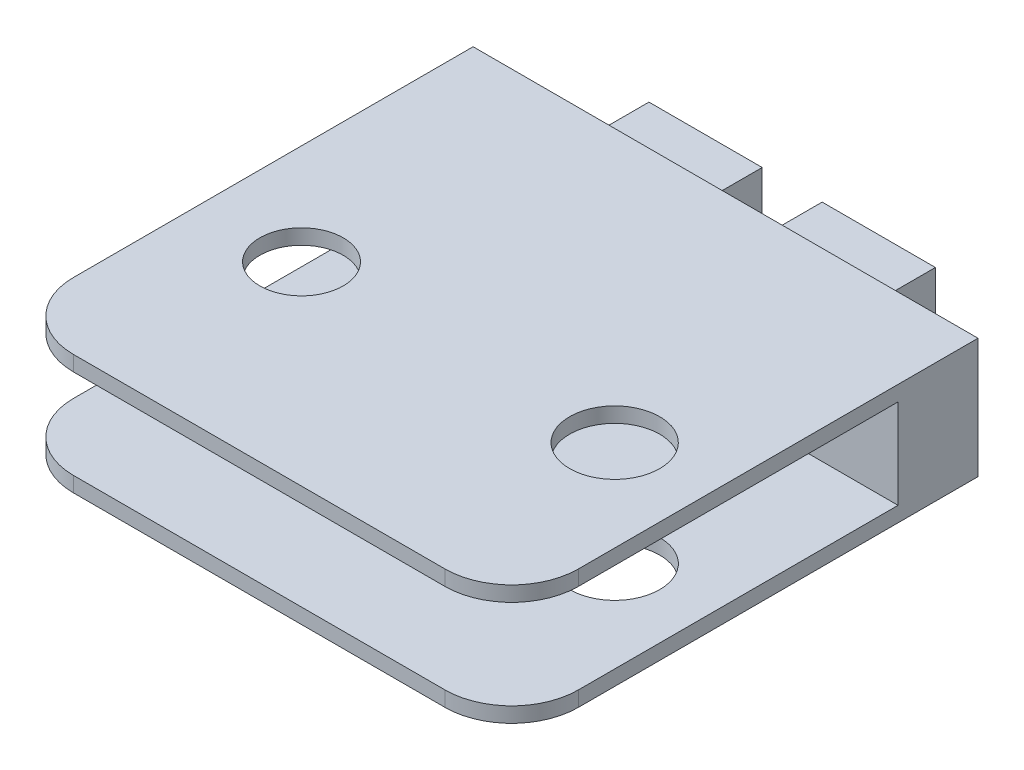
SolidWorks part; units mm, degrees
material "ABS"
ref_plane "Front Plane" through (0, 0, 0) normal (0, 0, 1) x (1, 0, 0)
ref_plane "Top Plane" through (0, 0, 0) normal (0, 1, 0) x (1, 0, 0)
ref_plane "Right Plane" through (0, 0, 0) normal (1, 0, 0) x (0, 0, -1)
sketch "Sketch1" plane through (0, 0, 0) normal (0, 0, 1) x (1, 0, 0)
  line L0 (0, 13.4339) -> (0, -20.6258) construction
  line L1 (-37.895, 9) -> (37.895, 9)
  line L2 (-37.895, 9) -> (-37.895, -9)
  line L3 (-37.895, -9) -> (37.895, -9)
  line L4 (37.895, 9) -> (37.895, -9)
  line L5 (-37.895, 9) -> (37.895, -9) construction
  line L6 (-37.895, -9) -> (37.895, 9) construction
  point P0 (0, 0)
  dimension "D1" = 18
  dimension "D2" = 75.79
extrude "Boss-Extrude1" add sketch "Sketch1" along normal blind 60
sketch "Sketch2" plane through (0, 0, 60) normal (0, 0, 1) x (1, 0, 0)
  line L0 (-37.895, 9) -> (-37.895, -9) construction
  line L1 (-37.895, 6.725) -> (37.895, 6.725)
  line L2 (-37.895, 6.725) -> (-37.895, -6.725)
  line L3 (-37.895, -6.725) -> (37.895, -6.725)
  line L4 (37.895, 6.725) -> (37.895, -6.725)
  line L5 (37.895, -9) -> (37.895, 9) construction
  line L6 (-47.3969, 0) -> (65.922, 0) construction
  line L7 (0, 11.7754) -> (0, -15.2518) construction
  point P13 (0, 0)
  dimension "D1" = 6.725
  dimension "D2" = 6.725
extrude "Cut-Extrude1" cut sketch "Sketch2" against normal blind 58
ref_plane "Plane1" through (-37.895, 9, 0) normal (-1, 0, 0) x (0, 0, 1)
sketch "Sketch6" plane through (0, 0, 0) normal (0, 0, -1) x (-1, 0, 0)
  line L1 (-37.895, 9) -> (37.895, 9)
  line L2 (-37.895, 9) -> (-37.895, -9)
  line L3 (-37.895, -9) -> (37.895, -9)
  line L4 (37.895, 9) -> (37.895, -9)
sketch "Sketch7" plane through (0, 9, 0) normal (0, 1, 0) x (1, 0, 0)
  line L0 (-48.5502, -30.8441) -> (50.5828, -30.8441) construction
  circle A0 centre (-22.8078, -30.8441) radius 6.2609
  circle A1 centre (24.1991, -30.8441) radius 6.7609
  dimension "D1" = 0
extrude "Cut-Extrude3" cut sketch "Sketch7" against normal through all
extrude "Boss-Extrude2" add sketch "Sketch6" along normal blind 10
sketch "Sketch8" plane through (0, 0, -10) normal (0, 0, -1) x (-1, 0, 0)
  line L0 (0, 22.3829) -> (0, -24.7432) construction
  line L1 (-45.8679, 0) -> (49.2994, 0) construction
  line L3 (-21.5, 5) -> (-4.5, 5)
  line L4 (-21.5, 5) -> (-21.5, -5)
  line L5 (-21.5, -5) -> (-4.5, -5)
  line L6 (-4.5, 5) -> (-4.5, -5)
  line L7 (-21.5, 5) -> (-4.5, -5) construction
  line L8 (-21.5, -5) -> (-4.5, 5) construction
  line L9 (4.5, 5) -> (21.5, 5)
  line L10 (4.5, 5) -> (4.5, -5)
  line L11 (4.5, -5) -> (21.5, -5)
  line L12 (21.5, 5) -> (21.5, -5)
  line L13 (4.5, 5) -> (21.5, -5) construction
  line L14 (4.5, -5) -> (21.5, 5) construction
  point P5 (-13, 0)
  point P10 (13, 0)
  dimension "D1" = 4.5
  dimension "D2" = 4.5
  dimension "D3" = 17
  dimension "D4" = 17
  dimension "D5" = 10
  dimension "1" = 10
extrude "Boss-Extrude3" add sketch "Sketch8" along normal blind 10
fillet "Fillet1" radius 10 4 edges at (37.895, 7.8625, 60) (37.895, -7.8625, 60) (-37.895, -7.8625, 60) (-37.895, 7.8625, 60)
sketch "Sketch9" plane through (0, 0, 60) normal (0, 0, 1) x (1, 0, 0)
  line L0 (-27.895, -9) -> (27.895, -9) construction
  line L1 (-16.1389, 9) -> (16.1389, 9)
  line L2 (-16.1389, 9) -> (-16.1389, -9)
  line L3 (-16.1389, -9) -> (16.1389, -9)
  line L4 (16.1389, 9) -> (16.1389, -9)
  line L5 (-16.1389, 9) -> (16.1389, -9) construction
  line L6 (-16.1389, -9) -> (16.1389, 9) construction
  point P0 (0, 0)
extrude "Boss-Extrude4" [suppressed] add sketch "Sketch9" along normal blind 3
sketch "Sketch10" plane through (0, 9, 0) normal (0, 1, 0) x (1, 0, 0)
  circle A0 centre (0, -41.8825) radius 1.5
extrude "Cut-Extrude4" [suppressed] cut sketch "Sketch10" against normal blind 2
sketch "Sketch11" plane through (0, 9, 0) normal (0, 1, 0) x (1, 0, 0)
  line L1 (-6.0227, -42.4877) -> (-6.0227, -46.4121)
  line L2 (-8.0227, -61.6545) -> (8.0227, -61.6545)
  line L3 (-8.0227, -61.6545) -> (-8.0227, -59.2714)
  line L4 (-8.0227, -59.2714) -> (8.0227, -59.2714)
  line L6 (8.0227, -61.6545) -> (8.0227, -59.2714)
  line L7 (-8.0227, -61.6545) -> (8.0227, -59.2714) construction
  line L8 (-8.0227, -59.2714) -> (8.0227, -61.6545) construction
  line L9 (-8.0227, -42.4877) -> (-6.0227, -42.4877)
  line L10 (-8.0227, -42.4877) -> (-8.0227, -46.4121)
  line L11 (-8.0227, -46.4121) -> (-6.0227, -46.4121)
  line L12 (8.0227, -42.4877) -> (8.0227, -46.4121)
  line L13 (-8.0227, -42.4877) -> (-6.0227, -42.9769) construction
  line L14 (-8.0227, -46.4121) -> (-6.0227, -45.923) construction
  line L15 (6.0227, -42.4877) -> (6.0227, -46.4121)
  line L16 (6.0227, -42.4877) -> (8.0227, -42.4877)
  line L17 (6.0227, -45.923) -> (8.0227, -46.4121) construction
  line L18 (6.0227, -42.9769) -> (8.0227, -42.4877) construction
  line L19 (6.0227, -46.4121) -> (8.0227, -46.4121)
  point P0 (0, -60.4629)
  point P5 (0, -44.4499)
  dimension "D1" = 2
  dimension "D2" = 2
extrude "Boss-Extrude5" [suppressed] add sketch "Sketch11" along normal blind 2
sketch "Sketch12" [suppressed] plane through (0, 0, 61.6545) normal (0, 0, 1) x (1, 0, 0)
  line L0 (7.1, 9) -> (7.1, 10.2)
  line L1 (16.1389, 9) -> (-16.1389, 9) construction
  line L2 (7.1, 10.2) -> (7.1, 9) construction
  line L3 (7.1, 10.2) -> (-7.1, 10.2)
  line L4 (7.1, 9) -> (7.1, 10.2)
  line L5 (-7.1, 10.2) -> (-7.1, 9)
  line L6 (-7.1, 9) -> (7.1, 9)
  line M1 (-8.0227, 9) -> (8.0227, 9)
extrude "Cut-Extrude5" [suppressed] cut sketch "Sketch12" against normal blind 27 contours L3 L5 L0 M1
